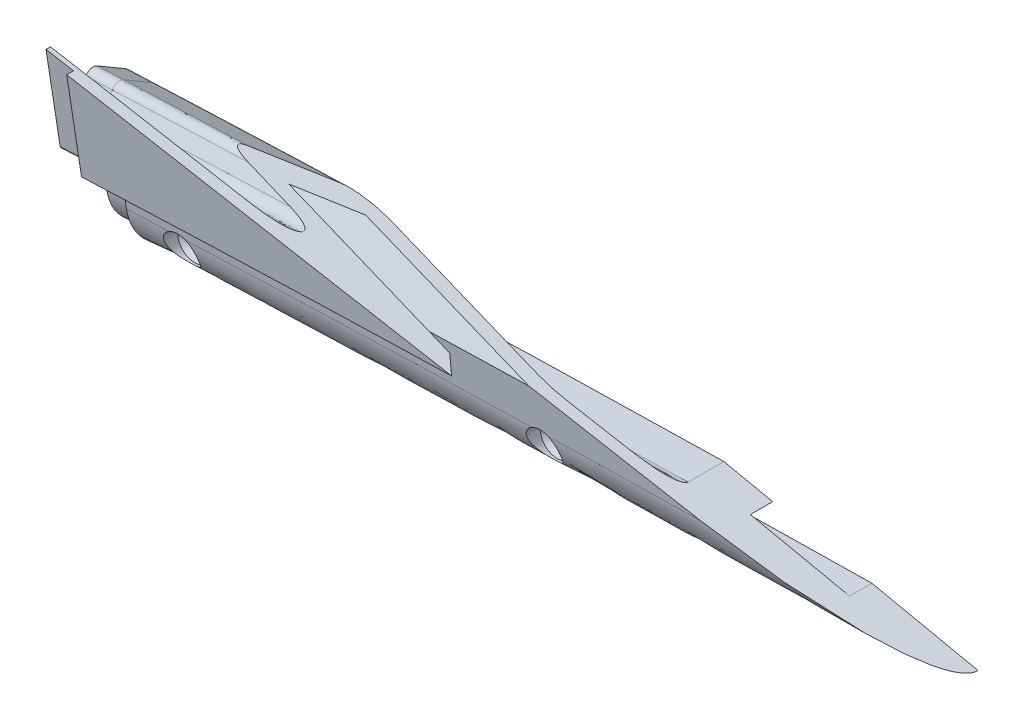
SolidWorks part; units mm, degrees
ref_plane "Front Plane" through (0, 0, 0) normal (0, 0, 1) x (1, 0, 0)
ref_plane "Top Plane" through (0, 0, 0) normal (0, 1, 0) x (1, 0, 0)
ref_plane "Right Plane" through (0, 0, 0) normal (1, 0, 0) x (0, 0, -1)
ref_plane "Plane3" through (-117.056, -3.871, 0) normal (0.9995, 0.0331, 0) x (0, 0, -1)
sketch "Sketch2" plane through (-117.056, -3.871, 0) normal (0.9995, 0.0331, 0) x (0, 0, -1)
  line L0 (-101.6, -41.1511) -> (-101.6, -45.9265)
  line L1 (-101.6, -41.1511) -> (-101.6, -45.9265)
  line L2 (-106.68, -45.9265) -> (-106.68, -50.6257)
  line L3 (-106.68, -45.9265) -> (-106.68, -50.6257)
  line L4 (-101.6, -50.6257) -> (-106.68, -50.6257)
  line L5 (-101.6, -50.6257) -> (-106.68, -50.6257)
  line L6 (-101.6, -50.6257) -> (-101.6, -56.1377)
  line L7 (-101.6, -50.6257) -> (-101.6, -56.1377)
  line L8 (-106.68, -45.9265) -> (-101.6, -45.9265)
  line L9 (-106.68, -45.9265) -> (-101.6, -45.9265)
  line L10 (-106.8705, -50.8162) -> (-108.9961, -53.9781) construction
  line L11 (-101.7905, -43.196) -> (-101.7905, -45.736)
  line L12 (-106.8705, -45.736) -> (-101.7905, -45.736)
  line L13 (-106.8705, -45.736) -> (-106.8705, -50.8162)
  line L14 (-101.7905, -50.8162) -> (-106.8705, -50.8162)
  line L15 (-101.7905, -50.8162) -> (-101.7905, -56.1377)
  line L16 (-101.7905, -43.196) -> (-101.6, -43.196)
  line L17 (-101.7905, -41.1511) -> (-101.7905, -45.736) construction
  line L18 (-120.8053, -33.0481) -> (-115.57, -36.0708)
  line L19 (-120.8053, -33.0481) -> (-115.57, -36.0708)
  line L20 (-109.601, -25.7318) -> (-114.8363, -22.709)
  line L21 (-109.601, -25.7318) -> (-114.8363, -22.709)
  line L22 (-114.8363, -22.709) -> (-120.8053, -33.0481)
  line L23 (-114.8363, -22.709) -> (-120.8053, -33.0481)
  line L24 (-115.57, -36.0708) -> (-109.601, -25.7318)
  line L25 (-115.57, -36.0708) -> (-109.601, -25.7318)
  line L26 (-115.57, -36.0708) -> (-114.523, -44.9291)
  line L28 (-118.1876, -34.5595) -> (-112.2186, -24.2204) construction
  line L29 (-114.6403, -39.5406) -> (-107.0838, -26.4518)
  line L30 (-107.7811, -23.8496) -> (-114.1162, -20.1918)
  line L31 (-116.7185, -20.8891) -> (-124.2749, -33.9778)
  line L33 (-106.1314, -24.8021) -> (-115.766, -19.2393) construction
  line L34 (-115.766, -19.2393) -> (-124.2749, -33.9778) construction
  line L35 (-114.6403, -39.5406) -> (-106.1314, -24.8021) construction
  line L36 (-124.2749, -33.9778) -> (-114.6403, -39.5406) construction
  line L37 (-112.9486, -36.6103) -> (-112.1701, -43.196)
  line L38 (-124.2749, -33.9778) -> (-128.0422, -2.1051)
  line L39 (-128.0422, -2.1051) -> (-132.6063, -0.4439)
  line L40 (-50.8, 0.7495) -> (-2184.4, 0.7495)
  line L41 (-125.822, 0.7495) -> (-133.442, 0.7495)
  line L42 (-122.1519, -30.3004) -> (-125.822, 0.7495)
  arc A0 (-114.523, -44.9291) -> (-101.7905, -56.1377) centre (-101.9108, -43.4383) ccw
  arc A2 (-114.1162, -20.1918) -> (-116.7185, -20.8891) centre (-115.0687, -21.8416) ccw
  arc A3 (-107.0838, -26.4518) -> (-107.7811, -23.8496) centre (-108.7336, -25.4993) ccw
  arc A4 (-133.442, 0.7495) -> (-132.6063, -0.4439) centre (-132.172, 0.7495) ccw
  point P41 (-133.442, 0.7495)
  dimension "D2" = 25.4
  dimension "D6" = 1.905
  dimension "D8" = 2.54
  dimension "D4" = 2.54
  dimension "D5" = 2.54
  dimension "D7" = 2.54
  dimension "D9" = 2.54
  dimension "D10" = 20
  dimension "D11" = 7.62
  dimension "D12" = 3.81
  dimension "D3" = 0.1905
sketch "Sketch3" plane through (0, 0, 101.6) normal (0, 0, 1) x (1, 0, 0)
  arc A0 (622.1039, -83.1998) -> (-622.1039, -83.1998) centre (0, -4954.4862) ccw construction
  arc A1 (622.1039, -83.1998) -> (-622.1039, -83.1998) centre (0, -4954.4862) ccw
sketch "Sketch4" plane through (-117.3306, 4.4304, 1117.6) normal (0.9995, 0.0331, 0) x (0, 0, -1)
  line L29 (1009.8189, -32.1556) -> (1003.4838, -28.4978) construction
  line L32 (1000.8815, -29.1951) -> (993.3251, -42.2838) construction
  line L35 (993.3251, -42.2838) -> (989.5578, -10.4111) construction
  line L50 (995.4481, -38.6064) -> (991.778, -7.5565) construction
  line L51 (1002.03, -44.3768) -> (1003.077, -53.235) construction
  line L52 (1015.8095, -59.1222) -> (1015.8095, -64.4437) construction
  line L53 (1015.8095, -59.1222) -> (1010.7295, -59.1222) construction
  line L54 (1010.7295, -54.042) -> (1010.7295, -59.1222) construction
  line L55 (1010.7295, -54.042) -> (1015.8095, -54.042) construction
  line L56 (1015.8095, -51.502) -> (1015.8095, -54.042) construction
  line L57 (1015.8095, -51.502) -> (1016, -51.502) construction
  line L58 (1004.6514, -44.9163) -> (1005.4299, -51.502) construction
  line L60 (1002.7637, -31.015) -> (996.7947, -41.3541) construction
  line L61 (1007.999, -34.0377) -> (1002.7637, -31.015) construction
  line L62 (1002.03, -44.3768) -> (1007.999, -34.0377) construction
  line L64 (991.5295, -5.4538) -> (988.9718, -5.4538)
  line L69 (1009.8189, -32.1556) -> (1003.4838, -28.4978)
  line L70 (1000.8815, -29.1951) -> (999.2724, -31.9822)
  line L71 (993.3251, -42.2838) -> (988.9718, -5.4538)
  line L74 (994.5502, -31.0104) -> (991.5295, -5.4538)
  line L75 (1002.03, -44.3768) -> (1003.077, -53.235)
  line L76 (1015.8095, -59.1222) -> (1015.8095, -64.4437)
  line L77 (1015.8095, -59.1222) -> (1010.7295, -59.1222)
  line L78 (1010.7295, -54.042) -> (1010.7295, -59.1222)
  line L79 (1010.7295, -54.042) -> (1015.8095, -54.042)
  line L80 (1015.8095, -51.502) -> (1015.8095, -54.042)
  line L81 (1015.8095, -51.502) -> (1007.6873, -51.502)
  line L82 (1004.7505, -45.7539) -> (1005.1649, -49.2601)
  line L84 (1002.7637, -31.015) -> (996.7947, -41.3541)
  line L85 (1007.999, -34.0377) -> (1002.7637, -31.015)
  line L86 (1002.03, -44.3768) -> (1007.999, -34.0377)
  line L87 (996.7947, -41.3541) -> (993.3251, -42.2838)
  line L88 (1005.0732, -44.1858) -> (1010.5162, -34.7578)
  arc A8 (1010.5162, -34.7578) -> (1009.8189, -32.1556) centre (1008.8664, -33.8053) ccw construction
  arc A9 (1003.4838, -28.4978) -> (1000.8815, -29.1951) centre (1002.5313, -30.1476) ccw construction
  arc A11 (1003.077, -53.235) -> (1015.8095, -64.4437) centre (1015.6892, -51.7443) ccw construction
  arc A12 (1010.5162, -34.7578) -> (1009.8189, -32.1556) centre (1008.8664, -33.8053) ccw
  arc A13 (1003.4838, -28.4978) -> (1000.8815, -29.1951) centre (1002.5313, -30.1476) ccw
  arc A15 (1003.077, -53.235) -> (1015.8095, -64.4437) centre (1015.6892, -51.7443) ccw
  arc A16 (1005.1649, -49.2601) -> (1007.6873, -51.502) centre (1007.6873, -48.962) ccw
  arc A17 (1004.7505, -45.7539) -> (1005.0732, -44.1858) centre (1007.2729, -45.4558) cw
  arc A18 (994.5502, -31.0104) -> (999.2724, -31.9822) centre (997.0727, -30.7122) ccw
  dimension "D2" = 2.54
  dimension "D1" = 36.83
sweep "Sweep3" add profiles "Sketch4" path "Sketch3"
sketch "Sketch5" plane through (0, 0, 101.7905) normal (0, 0, -1) x (-1, 0, 0)
  line L0 (211.6509, -4.1577) -> (0, -4954.4862) construction
  line L1 (0, -4954.4862) -> (22.6652, -1.2703) construction
  line L2 (117.0808, -1.0187) -> (0, -4954.4862) construction
  arc A1 (628.0925, -39.606) -> (-627.2635, -39.5001) centre (0, -4954.4862) ccw construction
  point P16 (117.0808, -1.0187)
ref_plane "Plane1" through (-211.4422, -9.0402, 0) normal (-0.9991, -0.0427, 0) x (0.0427, -0.9991, 0)
ref_plane "Plane2" through (-22.6706, -0.1037, 0) normal (1, 0.0046, 0) x (-0.0046, 1, 0)
other "SurfaceCut1"
other "SurfaceCut2"
sketch "Sketch8" plane through (-117.056, -3.871, 0) normal (0.9995, 0.0331, 0) x (0, 0, -1)
  line L0 (-106.8705, -50.8162) -> (-106.8705, -45.736)
  line L1 (-106.8705, -50.8162) -> (-106.8705, -45.736)
  line L2 (-106.8705, -48.2761) -> (-119.5705, -48.2761)
  line L3 (-119.5705, -48.2761) -> (-119.5705, -44.4661)
  line L4 (-119.5705, -44.4661) -> (-110.6805, -44.4661)
  line L5 (-110.6805, -44.4661) -> (-108.7755, -46.3711)
  line L6 (-108.7755, -46.3711) -> (-106.8705, -46.3711)
  line L7 (-119.5705, -48.2761) -> (-117.7248, -48.2761) construction
  dimension "D1" = 1.905
  dimension "D2" = 1.905
  dimension "D3" = 12.7
  dimension "D4" = 45
  dimension "D5" = 3.81
revolve "Cut-Revolve1" cut sketch "Sketch8" angle 360 about L7
sketch "Sketch9" plane through (0, 0, 106.8705) normal (0, 0, -1) x (-1, 0, 0)
  line L0 (198.0737, -52.2212) -> (197.8686, -57.297) construction
  line L1 (32.934, -48.3318) -> (32.8999, -53.4117) construction
  arc A1 (209.5755, -52.6994) -> (22.4502, -48.2726) centre (0, -4954.4862) ccw construction
  arc A2 (209.3585, -57.7748) -> (22.4269, -53.3526) centre (0, -4954.4862) ccw construction
  point P8 (197.9712, -54.7591)
  point P11 (0, -4954.4862)
  point P16 (115.4604, -52.1207)
  dimension "D1" = 82.55
  dimension "D2" = 82.55
sketch "Sketch10" plane through (0, 0, 106.8705) normal (0, 0, -1) x (-1, 0, 0)
  line L0 (32.934, -48.3318) -> (32.8999, -53.4117) construction
  point P0 (32.917, -50.8717)
  point P1 (197.9712, -54.7591)
pattern_sketch "Sketch-Pattern1" of "Cut-Revolve1" driven by "Sketch10"
sketch "Sketch12" plane through (0, 0, 101.7905) normal (0, 0, -1) x (-1, 0, 0)
  line L0 (22.4618, -45.7328) -> (0, -4954.4862) construction
  line L1 (0, -4954.4862) -> (16.4928, -45.7091) construction
  arc A1 (209.684, -50.1619) -> (22.4618, -45.7328) centre (0, -4954.4862) ccw construction
  arc A2 (22.4618, -45.7328) -> (16.4928, -45.7091) centre (0, -4954.4862) ccw
  dimension "D1" = 5.969
sketch "Sketch11" plane through (-22.6706, -0.1037, 0) normal (1, 0.0046, 0) x (0, 0, -1)
  line L0 (-127.4772, 0.4166) -> (-123.2949, -34.9658)
  line L1 (-123.2949, -34.9658) -> (-121.5584, -34.5006)
  line L2 (-121.5584, -34.5006) -> (-115.5722, -24.132)
  line L3 (-114.7047, -23.8996) -> (-108.5896, -27.4302)
  line L4 (-108.3571, -28.2976) -> (-114.3903, -38.7475)
  line L5 (-114.3903, -38.7475) -> (-113.3879, -47.2283)
  line L6 (-127.4931, 0.5508) -> (-123.2949, -34.9658) construction
  line L7 (-101.7905, -58.5707) -> (-101.7905, -57.4277)
  line L8 (-101.7905, -53.2494) -> (-101.7905, -58.5707) construction
  line L9 (-101.7905, -57.4277) -> (-101.8013, -57.4277)
  line L10 (-115.2547, -23.5821) -> (-108.0396, -27.7477) construction
  line L11 (-108.0396, -27.7477) -> (-114.3903, -38.7475) construction
  line L12 (-121.5584, -34.5006) -> (-115.2547, -23.5821) construction
  line L18 (-126.0705, 0.4166) -> (-128.6282, 0.4166)
  line L19 (-128.6282, 0.4166) -> (-124.2749, -36.4117)
  line L20 (-124.2749, -36.4117) -> (-120.8053, -35.4821)
  line L21 (-120.8053, -35.4821) -> (-114.8363, -25.1435)
  line L22 (-114.8363, -25.1435) -> (-109.601, -28.1661)
  line L23 (-109.601, -28.1661) -> (-115.57, -38.5047)
  line L24 (-115.57, -38.5047) -> (-114.523, -47.3625)
  line L25 (-101.7905, -58.5707) -> (-101.7905, -53.2494)
  line L26 (-101.7905, -53.2494) -> (-106.8705, -53.2494)
  line L27 (-106.8705, -53.2494) -> (-106.8705, -48.1694)
  line L28 (-106.8705, -48.1694) -> (-101.7905, -48.1694)
  line L29 (-101.7905, -48.1694) -> (-101.7905, -45.6295)
  line L30 (-101.7905, -45.6295) -> (-109.9127, -45.6295)
  line L31 (-112.4351, -43.3877) -> (-112.8495, -39.8818)
  line L32 (-112.5268, -38.3137) -> (-107.0838, -28.8861)
  line L33 (-107.781, -26.284) -> (-114.1162, -22.6264)
  line L34 (-116.7185, -23.3237) -> (-118.3276, -26.1106)
  line L35 (-123.0498, -25.1389) -> (-126.0705, 0.4166)
  line L36 (-127.4772, 0.4166) -> (-128.6282, 0.4166)
  line L37 (-128.6282, 0.4166) -> (-124.2749, -36.4117)
  line L38 (-124.2749, -36.4117) -> (-120.8053, -35.4821)
  line L39 (-120.8053, -35.4821) -> (-114.8363, -25.1435)
  line L40 (-114.8363, -25.1435) -> (-109.601, -28.1661)
  line L41 (-109.601, -28.1661) -> (-115.57, -38.5047)
  line L42 (-115.57, -38.5047) -> (-114.523, -47.3625)
  arc A0 (-108.5896, -27.4302) -> (-108.3571, -28.2976) centre (-108.9071, -27.9801) cw
  arc A1 (-115.5722, -24.132) -> (-114.7047, -23.8996) centre (-115.0222, -24.4495) cw
  arc A4 (-112.4351, -43.3877) -> (-109.9127, -45.6295) centre (-109.9127, -43.0896) ccw
  arc A5 (-112.5268, -38.3137) -> (-112.8495, -39.8818) centre (-110.3273, -39.5836) ccw
  arc A6 (-107.0838, -28.8861) -> (-107.781, -26.284) centre (-108.7335, -27.9337) ccw
  arc A7 (-114.1162, -22.6264) -> (-116.7185, -23.3237) centre (-115.0687, -24.2762) ccw
  spline S0 degree 1 poles (-113.3879, -47.2283) (-101.8013, -57.4277) knots 0 0 1 1 construction
  spline S1 degree 3 poles (-113.3879, -47.2283) (-113.3048, -47.9312) (-113.0054, -49.3311) (-111.9316, -51.9219) (-109.7159, -54.7453) (-106.0351, -56.9462) (-103.2019, -57.441) (-101.8013, -57.4277) knots 0 0 0 0 0.125 0.25 0.5 0.75 1 1 1 1
  spline S2 degree 3 poles (1806.7112, 500.6593) (415.3182, 185.4237) (-128.7728, 19.3055) (-114.2511, -48.8979) (-114.1523, -49.2753) (-113.8076, -50.3831) (-113.513, -51.0943) (-112.7943, -52.462) (-112.3662, -53.122) (-111.4114, -54.3345) (-110.8822, -54.8938) (-110.0099, -55.6614) (-109.7043, -55.9064) (-109.0766, -56.3638) (-108.7542, -56.5768) (-107.762, -57.1694) (-107.0674, -57.5033) (-105.9744, -57.9099) (-105.6018, -58.0293) (-104.8546, -58.2314) (-104.4782, -58.315) (-51.6561, -67.5542) (53.4105, 250.9973) (369.459, 1883.4824) knots -11.048432 -11.048432 -11.048432 -11.048432 0.0625 0.0625 0.125 0.125 0.25 0.25 0.375 0.375 0.5 0.5 0.5625 0.5625 0.625 0.625 0.75 0.75 0.8125 0.8125 0.875 0.875 9.519326 9.519326 9.519326 9.519326 only from (-114.523, -47.3625) to (-101.7905, -58.5707)
  spline S3 degree 3 poles (-966.8365, -555.2861) (-146.5253, 43.3444) (-110.7563, -19.4508) (-119.0219, -26.9033) (-119.2485, -27.051) (-119.7291, -27.2663) (-119.9898, -27.337) (-120.3827, -27.3799) (-120.5144, -27.384) (-120.779, -27.3716) (-120.9121, -27.3548) (-121.1705, -27.3014) (-121.297, -27.2648) (-121.5443, -27.1719) (-121.6661, -27.1149) (-121.896, -26.9844) (-122.0051, -26.9107) (-122.2115, -26.7465) (-122.3097, -26.6551) (-122.5785, -26.3621) (-122.7254, -26.141) (-131.5662, -6.8587) (104.7841, 84.3424) (817.0786, 315.6789) knots -5.03449 -5.03449 -5.03449 -5.03449 0.125 0.125 0.25 0.25 0.375 0.375 0.4375 0.4375 0.5 0.5 0.5625 0.5625 0.625 0.625 0.6875 0.6875 0.75 0.75 0.875 0.875 10.718854 10.718854 10.718854 10.718854 only from (-118.3276, -26.1106) to (-123.0498, -25.1389)
  spline S4 degree 3 poles (-114.523, -47.3625) (-114.4771, -47.7503) (-114.4136, -48.1349) (-114.2511, -48.8979) (-114.1523, -49.2753) (-113.8076, -50.3831) (-113.513, -51.0943) (-112.7943, -52.462) (-112.3662, -53.122) (-111.4114, -54.3345) (-110.8822, -54.8938) (-110.0099, -55.6614) (-109.7043, -55.9064) (-109.0766, -56.3638) (-108.7542, -56.5768) (-107.762, -57.1694) (-107.0674, -57.5033) (-105.9744, -57.9099) (-105.6018, -58.0293) (-104.8546, -58.2314) (-104.4782, -58.315) (-103.3407, -58.514) (-102.5713, -58.5781) (-101.7905, -58.5707) knots 0 0 0 0 0.0625 0.0625 0.125 0.125 0.25 0.25 0.375 0.375 0.5 0.5 0.5625 0.5625 0.625 0.625 0.75 0.75 0.8125 0.8125 0.875 0.875 1 1 1 1
  dimension "D3" = 0.635
  dimension "D1" = 0
  dimension "D2" = 1.143
sweep "Sweep4" add profiles "Sketch11" path "Sketch12"
sketch "Sketch14" plane through (-211.4422, -9.0402, 0) normal (-0.9991, -0.0427, 0) x (0, 0, 1)
  line L0 (113.0095, -42.7133) -> (113.9971, -34.3581)
  line L1 (113.9971, -34.3581) -> (107.5192, -23.138)
  line L2 (107.5192, -23.138) -> (115.3941, -18.5914)
  line L3 (115.3941, -18.5914) -> (121.8095, -29.7031)
  line L4 (121.8095, -29.7031) -> (122.9682, -30.0136)
  line L5 (122.9682, -30.0136) -> (127.1147, 5.0658)
  line L18 (128.6282, 4.8869) -> (126.0705, 4.8869)
  line L19 (126.0705, 4.8869) -> (123.0498, -20.6686)
  line L20 (118.3276, -21.6403) -> (116.7185, -18.8534)
  line L21 (114.1162, -18.1561) -> (107.7811, -21.8137)
  line L22 (107.0838, -24.4158) -> (112.5268, -33.8434)
  line L23 (112.8495, -35.4115) -> (112.4351, -38.9175)
  line L24 (109.9127, -41.1592) -> (101.7905, -41.1592)
  line L25 (101.7905, -41.1592) -> (101.7905, -43.6991)
  line L26 (101.7905, -43.6991) -> (106.8705, -43.6991)
  line L27 (106.8705, -43.6991) -> (106.8705, -48.7791)
  line L28 (106.8705, -48.7791) -> (101.7905, -48.7791)
  line L29 (101.7905, -48.7791) -> (101.7905, -54.1004)
  line L30 (114.523, -42.8922) -> (115.57, -34.0344)
  line L31 (115.57, -34.0344) -> (109.601, -23.6958)
  line L32 (109.601, -23.6958) -> (114.8363, -20.6732)
  line L33 (114.8363, -20.6732) -> (120.8053, -31.0118)
  line L34 (120.8053, -31.0118) -> (124.2749, -31.9414)
  line L35 (124.2749, -31.9414) -> (128.6282, 4.8869)
  line L36 (128.6282, 4.8869) -> (126.0705, 4.8869)
  line L37 (126.0705, 4.8869) -> (123.0498, -20.6686)
  line L38 (118.3276, -21.6403) -> (116.7185, -18.8534)
  line L39 (114.1162, -18.1561) -> (107.7811, -21.8137)
  line L40 (107.0838, -24.4158) -> (112.5268, -33.8434)
  line L41 (112.8495, -35.4115) -> (112.4351, -38.9175)
  line L42 (109.9127, -41.1592) -> (101.7905, -41.1592)
  line L43 (101.7905, -41.1592) -> (101.7905, -43.6991)
  line L44 (101.7905, -43.6991) -> (106.8705, -43.6991)
  line L45 (106.8705, -43.6991) -> (106.8705, -48.7791)
  line L46 (106.8705, -48.7791) -> (101.7905, -48.7791)
  line L47 (101.7905, -48.7791) -> (101.7905, -54.1004)
  line L48 (114.523, -42.8922) -> (115.57, -34.0344)
  line L49 (115.57, -34.0344) -> (109.601, -23.6958)
  line L50 (109.601, -23.6958) -> (114.8363, -20.6732)
  line L51 (114.8363, -20.6732) -> (120.8053, -31.0118)
  line L52 (120.8053, -31.0118) -> (124.2749, -31.9414)
  line L53 (124.2749, -31.9414) -> (128.6282, 4.8869)
  arc A4 (116.7185, -18.8534) -> (114.1162, -18.1561) centre (115.0687, -19.8059) ccw
  arc A5 (107.7811, -21.8137) -> (107.0838, -24.4158) centre (108.7335, -23.4634) ccw
  arc A6 (112.8495, -35.4115) -> (112.5268, -33.8434) centre (110.3273, -35.1133) ccw
  arc A7 (109.9127, -41.1592) -> (112.4351, -38.9175) centre (109.9127, -38.6193) ccw
  arc A8 (116.7185, -18.8534) -> (114.1162, -18.1561) centre (115.0687, -19.8059) ccw
  arc A9 (107.7811, -21.8137) -> (107.0838, -24.4158) centre (108.7335, -23.4634) ccw
  arc A10 (112.8495, -35.4115) -> (112.5268, -33.8434) centre (110.3273, -35.1133) ccw
  arc A11 (109.9127, -41.1592) -> (112.4351, -38.9175) centre (109.9127, -38.6193) ccw
  spline S0 degree 1 poles (101.8049, -52.5765) (113.0095, -42.7133) knots 0 0 1 1 construction
  spline S1 degree 3 poles (101.8049, -52.5765) (102.4893, -52.583) (103.8689, -52.4674) (106.4858, -51.7551) (109.4658, -49.9761) (112.0284, -46.7154) (112.8505, -44.0584) (113.0095, -42.7133) knots 0 0 0 0 0.125 0.25 0.5 0.75 1 1 1 1
  spline S2 degree 3 poles (-1420.2451, -2589.1907) (7.5348, 76.4537) (129.3579, -7.252) (122.7249, -21.671) (122.575, -21.8961) (122.2185, -22.2837) (122.0069, -22.4517) (121.6628, -22.6462) (121.5435, -22.702) (121.2955, -22.795) (121.1665, -22.8321) (120.908, -22.8851) (120.7774, -22.9014) (120.5134, -22.9137) (120.3791, -22.9094) (120.1163, -22.8803) (119.987, -22.8557) (119.7325, -22.7864) (119.6063, -22.7412) (119.2436, -22.578) (119.0214, -22.433) (93.7379, 0.421) (581.1886, 448.0858) (2362.312, 1968.4478) knots -7.286241 -7.286241 -7.286241 -7.286241 0.125 0.125 0.25 0.25 0.375 0.375 0.4375 0.4375 0.5 0.5 0.5625 0.5625 0.625 0.625 0.6875 0.6875 0.75 0.75 0.875 0.875 16.766809 16.766809 16.766809 16.766809 only from (123.0498, -20.6686) to (118.3276, -21.6403)
  spline S3 degree 3 poles (-288.3388, 2916.9987) (-102.777, 757.3692) (19.5454, -60.9671) (103.3479, -54.0254) (103.7348, -53.9753) (104.8774, -53.7738) (105.6202, -53.5717) (107.068, -53.0324) (107.777, -52.6914) (109.1008, -51.8981) (109.7227, -51.4442) (110.5948, -50.6762) (110.8766, -50.4042) (111.4099, -49.8396) (111.662, -49.5468) (112.3757, -48.6378) (112.795, -47.9912) (113.3369, -46.9586) (113.5026, -46.6041) (113.7979, -45.8886) (113.9285, -45.5258) (132.5439, 14.5864) (-288.4354, 203.7302) (-2703.1014, 979.8882) knots -13.349036 -13.349036 -13.349036 -13.349036 0.0625 0.0625 0.125 0.125 0.25 0.25 0.375 0.375 0.5 0.5 0.5625 0.5625 0.625 0.625 0.75 0.75 0.8125 0.8125 0.875 0.875 11.030088 11.030088 11.030088 11.030088 only from (101.7905, -54.1004) to (114.523, -42.8922)
  spline S4 degree 3 poles (123.0498, -20.6686) (123.0184, -20.9338) (122.9449, -21.1927) (122.7249, -21.671) (122.575, -21.8961) (122.2185, -22.2837) (122.0069, -22.4517) (121.6628, -22.6462) (121.5435, -22.702) (121.2955, -22.795) (121.1665, -22.8321) (120.908, -22.8851) (120.7774, -22.9014) (120.5134, -22.9137) (120.3791, -22.9094) (120.1163, -22.8803) (119.987, -22.8557) (119.7325, -22.7864) (119.6063, -22.7412) (119.2436, -22.578) (119.0214, -22.433) (118.6267, -22.0763) (118.4611, -21.8716) (118.3276, -21.6403) knots 0 0 0 0 0.125 0.125 0.25 0.25 0.375 0.375 0.4375 0.4375 0.5 0.5 0.5625 0.5625 0.625 0.625 0.6875 0.6875 0.75 0.75 0.875 0.875 1 1 1 1
  spline S5 degree 3 poles (101.7905, -54.1004) (102.1809, -54.1041) (102.5705, -54.0898) (103.3479, -54.0254) (103.7348, -53.9753) (104.8774, -53.7738) (105.6202, -53.5717) (107.068, -53.0324) (107.777, -52.6914) (109.1008, -51.8981) (109.7227, -51.4442) (110.5948, -50.6762) (110.8766, -50.4042) (111.4099, -49.8396) (111.662, -49.5468) (112.3757, -48.6378) (112.795, -47.9912) (113.3369, -46.9586) (113.5026, -46.6041) (113.7979, -45.8886) (113.9285, -45.5258) (114.2702, -44.4227) (114.4313, -43.6677) (114.523, -42.8922) knots 0 0 0 0 0.0625 0.0625 0.125 0.125 0.25 0.25 0.375 0.375 0.5 0.5 0.5625 0.5625 0.625 0.625 0.75 0.75 0.8125 0.8125 0.875 0.875 1 1 1 1
  dimension "D1" = 0
  dimension "D2" = 1.524
sketch "Sketch15" plane through (-211.4422, -9.0402, 0) normal (-0.9991, -0.0427, 0) x (0, 0, 1)
  line L0 (113.0095, -42.7133) -> (113.9971, -34.3581) construction
  line L1 (113.9971, -34.3581) -> (107.5192, -23.138) construction
  line L2 (107.5192, -23.138) -> (115.3941, -18.5914) construction
  line L3 (115.3941, -18.5914) -> (121.8095, -29.7031) construction
  line L4 (121.8095, -29.7031) -> (122.9682, -30.0136) construction
  line L5 (122.9682, -30.0136) -> (127.1147, 5.0658) construction
  line L6 (113.0095, -42.7133) -> (113.9724, -34.5675)
  line L7 (113.8917, -34.1755) -> (107.5192, -23.138)
  line L8 (107.5192, -23.138) -> (115.3941, -18.5914)
  line L9 (115.3941, -18.5914) -> (121.678, -29.4753)
  line L10 (122.0636, -29.7712) -> (122.2594, -29.8237)
  line L11 (123.0543, -29.2848) -> (127.0936, 4.8869)
  line L12 (101.7905, -48.7791) -> (101.7905, -54.1004) construction
  line L13 (101.7905, -48.7791) -> (101.7905, -52.5765)
  line L14 (101.8049, -52.5765) -> (101.7905, -52.5765)
  line L18 (124.2749, -31.9414) -> (128.6282, 4.8869)
  line L19 (128.6282, 4.8869) -> (126.0705, 4.8869)
  line L20 (126.0705, 4.8869) -> (123.0498, -20.6686)
  line L21 (118.3276, -21.6403) -> (116.7185, -18.8534)
  line L22 (114.1162, -18.1561) -> (107.7811, -21.8137)
  line L23 (107.0838, -24.4158) -> (112.5268, -33.8434)
  line L24 (112.8495, -35.4115) -> (112.4351, -38.9175)
  line L25 (109.9127, -41.1592) -> (101.7905, -41.1592)
  line L26 (101.7905, -41.1592) -> (101.7905, -43.6991)
  line L27 (101.7905, -43.6991) -> (106.8705, -43.6991)
  line L28 (106.8705, -43.6991) -> (106.8705, -48.7791)
  line L29 (106.8705, -48.7791) -> (101.7905, -48.7791)
  line L30 (101.7905, -48.7791) -> (101.7905, -54.1004)
  line L31 (114.523, -42.8922) -> (115.57, -34.0344)
  line L32 (115.57, -34.0344) -> (109.601, -23.6958)
  line L33 (109.601, -23.6958) -> (114.8363, -20.6732)
  line L34 (114.8363, -20.6732) -> (120.8053, -31.0118)
  line L35 (120.8053, -31.0118) -> (124.2749, -31.9414)
  line L37 (127.0936, 4.8869) -> (126.0705, 4.8869)
  line L38 (126.0705, 4.8869) -> (123.0498, -20.6686)
  line L39 (118.3276, -21.6403) -> (116.7185, -18.8534)
  line L40 (114.1162, -18.1561) -> (107.7811, -21.8137)
  line L41 (107.0838, -24.4158) -> (112.5268, -33.8434)
  line L42 (112.8495, -35.4115) -> (112.4351, -38.9175)
  line L43 (109.9127, -41.1592) -> (101.7905, -41.1592)
  line L44 (101.7905, -41.1592) -> (101.7905, -43.6991)
  line L45 (101.7905, -43.6991) -> (106.8705, -43.6991)
  line L46 (106.8705, -43.6991) -> (106.8705, -48.7791)
  line L47 (106.8705, -48.7791) -> (101.7905, -48.7791)
  arc A0 (113.9724, -34.5675) -> (113.8917, -34.1755) centre (113.3418, -34.493) ccw
  arc A1 (121.678, -29.4753) -> (122.0636, -29.7712) centre (122.2279, -29.1578) ccw
  arc A2 (122.2594, -29.8237) -> (123.0543, -29.2848) centre (122.4237, -29.2103) ccw
  arc A4 (116.7185, -18.8534) -> (114.1162, -18.1561) centre (115.0687, -19.8059) ccw
  arc A5 (107.7811, -21.8137) -> (107.0838, -24.4158) centre (108.7335, -23.4634) ccw
  arc A6 (112.8495, -35.4115) -> (112.5268, -33.8434) centre (110.3273, -35.1133) ccw
  arc A7 (109.9127, -41.1592) -> (112.4351, -38.9175) centre (109.9127, -38.6193) ccw
  arc A8 (116.7185, -18.8534) -> (114.1162, -18.1561) centre (115.0687, -19.8059) ccw
  arc A9 (107.7811, -21.8137) -> (107.0838, -24.4158) centre (108.7335, -23.4634) ccw
  arc A10 (112.8495, -35.4115) -> (112.5268, -33.8434) centre (110.3273, -35.1133) ccw
  arc A11 (109.9127, -41.1592) -> (112.4351, -38.9175) centre (109.9127, -38.6193) ccw
  spline S0 degree 3 poles (1969.6766, 654.3437) (8.5109, 56.766) (75.3403, -60.2329) (106.4858, -51.7551) (109.4658, -49.9761) (134.2797, -18.4018) (-16.091, 107.1074) (-926.156, -1745.3361) knots -5.450838 -5.450838 -5.450838 -5.450838 0.125 0.25 0.5 0.75 7.512309 7.512309 7.512309 7.512309 only from (101.8049, -52.5765) to (113.0095, -42.7133) construction
  spline S1 degree 3 poles (101.8049, -52.5765) (102.4893, -52.583) (103.8689, -52.4674) (106.4858, -51.7551) (109.4658, -49.9761) (112.0284, -46.7154) (112.8505, -44.0584) (113.0095, -42.7133) knots 0 0 0 0 0.125 0.25 0.5 0.75 1 1 1 1
  spline S2 degree 3 poles (-1420.2451, -2589.1907) (7.5348, 76.4537) (129.3579, -7.252) (122.7249, -21.671) (122.575, -21.8961) (122.2185, -22.2837) (122.0069, -22.4517) (121.6628, -22.6462) (121.5435, -22.702) (121.2955, -22.795) (121.1665, -22.8321) (120.908, -22.8851) (120.7774, -22.9014) (120.5134, -22.9137) (120.3791, -22.9094) (120.1163, -22.8803) (119.987, -22.8557) (119.7325, -22.7864) (119.6063, -22.7412) (119.2436, -22.578) (119.0214, -22.433) (93.7379, 0.421) (581.1886, 448.0858) (2362.312, 1968.4478) knots -7.286241 -7.286241 -7.286241 -7.286241 0.125 0.125 0.25 0.25 0.375 0.375 0.4375 0.4375 0.5 0.5 0.5625 0.5625 0.625 0.625 0.6875 0.6875 0.75 0.75 0.875 0.875 16.766809 16.766809 16.766809 16.766809 only from (123.0498, -20.6686) to (118.3276, -21.6403)
  spline S3 degree 3 poles (-93.3253, 926.6784) (-10.5613, 232.0775) (53.1389, -58.1844) (103.3479, -54.0254) (103.7348, -53.9753) (104.8774, -53.7738) (105.6202, -53.5717) (107.068, -53.0324) (107.777, -52.6914) (109.1008, -51.8981) (109.7227, -51.4442) (110.5948, -50.6762) (110.8766, -50.4042) (111.4099, -49.8396) (111.662, -49.5468) (112.3757, -48.6378) (112.795, -47.9912) (113.3369, -46.9586) (113.5026, -46.6041) (113.7979, -45.8886) (113.9285, -45.5258) (125.9187, -6.8076) (-43.2917, 84.8615) (-804.6708, 350.8867) knots -7.947776 -7.947776 -7.947776 -7.947776 0.0625 0.0625 0.125 0.125 0.25 0.25 0.375 0.375 0.5 0.5 0.5625 0.5625 0.625 0.625 0.75 0.75 0.8125 0.8125 0.875 0.875 7.39364 7.39364 7.39364 7.39364 only from (101.7905, -54.1004) to (114.523, -42.8922)
  spline S4 degree 3 poles (123.0498, -20.6686) (123.0184, -20.9338) (122.9449, -21.1927) (122.7249, -21.671) (122.575, -21.8961) (122.2185, -22.2837) (122.0069, -22.4517) (121.6628, -22.6462) (121.5435, -22.702) (121.2955, -22.795) (121.1665, -22.8321) (120.908, -22.8851) (120.7774, -22.9014) (120.5134, -22.9137) (120.3791, -22.9094) (120.1163, -22.8803) (119.987, -22.8557) (119.7325, -22.7864) (119.6063, -22.7412) (119.2436, -22.578) (119.0214, -22.433) (118.6267, -22.0763) (118.4611, -21.8716) (118.3276, -21.6403) knots 0 0 0 0 0.125 0.125 0.25 0.25 0.375 0.375 0.4375 0.4375 0.5 0.5 0.5625 0.5625 0.625 0.625 0.6875 0.6875 0.75 0.75 0.875 0.875 1 1 1 1
  dimension "D2" = 0.635
  dimension "D1" = 0
sketch "Sketch16" plane through (0, 0, 101.7905) normal (0, 0, -1) x (-1, 0, 0)
  arc A0 (215.6474, -50.4205) -> (209.684, -50.1619) centre (0, -4954.4862) ccw
  arc A1 (209.684, -50.1619) -> (22.4618, -45.7328) centre (0, -4954.4862) ccw construction
  dimension "D1" = 5.969
sweep "Sweep5" add profiles "Sketch15" path "Sketch16"
ref_plane "Plane4" through (-13.1444, -61.9798, 0) normal (-0.2075, -0.9782, 0) x (-0.9782, 0.2075, 0)
other "SurfaceCut3"
